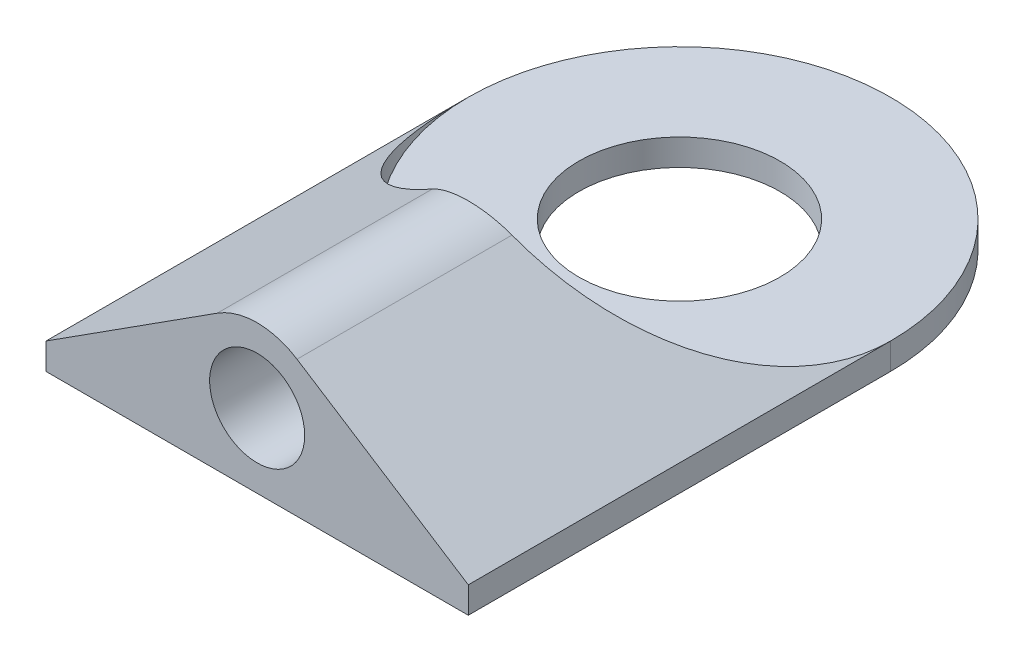
SolidWorks part; units mm, degrees
ref_plane "Front Plane" through (0, 0, 0) normal (0, 0, 1) x (1, 0, 0)
ref_plane "Top Plane" through (0, 0, 0) normal (0, 1, 0) x (1, 0, 0)
ref_plane "Right Plane" through (0, 0, 0) normal (1, 0, 0) x (0, 0, -1)
sketch "Sketch1" plane through (0, 0, 0) normal (0, 1, 0) x (1, 0, 0)
  line L0 (-40, 0) -> (-40, -80)
  line L1 (-40, -80) -> (40, -80)
  line L2 (40, -80) -> (40, 0)
  circle A0 centre (0, 0) radius 19.05
  arc A1 (40, 0) -> (-40, 0) centre (0, 0) ccw
  dimension "D1" = 38.1
  dimension "D2" = 80
  dimension "D3" = 80
extrude "Piston connection plate" add sketch "Sketch1" along normal blind 5
sketch "Sketch2" plane through (0, 0, 80) normal (0, 0, 1) x (1, 0, 0)
  line L0 (-40, 5) -> (40, 5) construction
  line L1 (-40, 5) -> (-7.5523, 25.7882)
  line L2 (40, 5) -> (7.5523, 25.7882)
  line L3 (-40, 5) -> (-40, 0)
  line L4 (-40, 0) -> (40, 0)
  line L5 (40, 0) -> (40, 5)
  circle A0 centre (0, 14) radius 9
  arc A1 (7.5523, 25.7882) -> (-7.5523, 25.7882) centre (0, 14) ccw
  dimension "D1" = 18
  dimension "D2" = 5
extrude "Platform tube link" add sketch "Sketch2" against normal blind 80
sketch "Sketch5" plane through (0, 0, 0) normal (0, 0, -1) x (-1, 0, 0)
  circle A0 centre (0, 14) radius 9 construction
  circle A1 centre (0, 14) radius 9
extrude "Rod cap (prevent rod from reaching piston)" add sketch "Sketch5" against normal blind 50
sketch "Sketch3" plane through (0, 0, 0) normal (0, -1, 0) x (1, 0, 0)
  circle A0 centre (0, 0) radius 19.05
  arc A1 (-19.05, 0) -> (19.05, 0) centre (0, 0) ccw construction
extrude "Cleanup cut 1" cut sketch "Sketch3" against normal through all both and the other way through all
sketch "Sketch4" plane through (0, 5, 0) normal (0, 1, 0) x (1, 0, 0)
  circle A0 centre (0, 0) radius 40
  arc A1 (40, 0) -> (-40, 0) centre (0, 0) ccw construction
extrude "Cleanup cut 2" cut sketch "Sketch4" along normal through all
